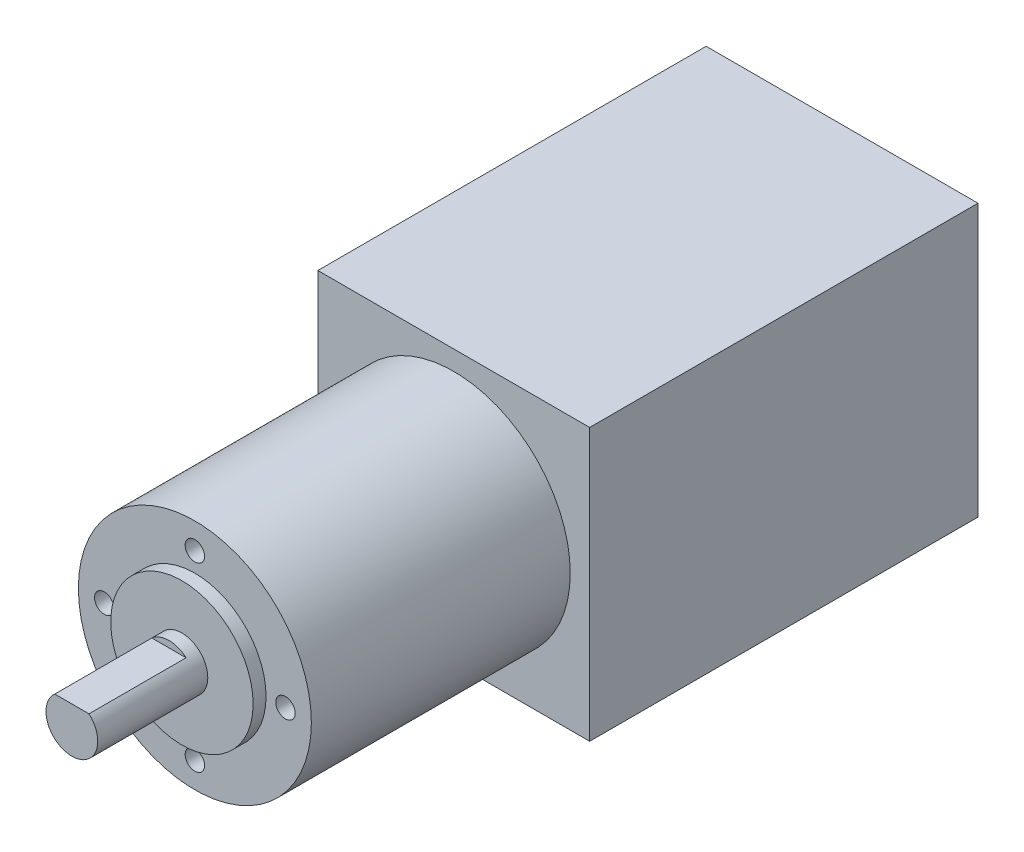
SolidWorks part; units mm, degrees
ref_plane "前视基准面" through (0, 0, 0) normal (0, 0, 1) x (1, 0, 0)
ref_plane "上视基准面" through (0, 0, 0) normal (0, 1, 0) x (1, 0, 0)
ref_plane "右视基准面" through (0, 0, 0) normal (1, 0, 0) x (0, 0, -1)
sketch "草图1" plane through (0, 0, 0) normal (0, 0, 1) x (1, 0, 0)
  line L1 (-21, 21) -> (21, 21)
  line L2 (-21, 21) -> (-21, -21)
  line L3 (-21, -21) -> (21, -21)
  line L4 (21, 21) -> (21, -21)
  line L5 (-21, 21) -> (21, -21) construction
  line L6 (-21, -21) -> (21, 21) construction
  point P0 (0, 0)
  dimension "D1" = 42
extrude "凸台-拉伸1" add sketch "草图1" along normal blind 60
sketch "草图2" plane through (0, 0, 60) normal (0, 0, 1) x (1, 0, 0)
  circle A0 centre (0, 0) radius 18
  dimension "D1" = 36
extrude "凸台-拉伸2" add sketch "草图2" along normal blind 40
sketch "草图3" plane through (0, 0, 100) normal (0, 0, 1) x (1, 0, 0)
  circle A0 centre (0, 0) radius 11
  dimension "D1" = 22
extrude "凸台-拉伸3" add sketch "草图3" along normal blind 2
sketch "草图4" plane through (0, 0, 102) normal (0, 0, 1) x (1, 0, 0)
  circle A0 centre (0, 0) radius 4
  dimension "D1" = 8
extrude "凸台-拉伸4" add sketch "草图4" along normal blind 17
sketch "草图5" plane through (0, 0, 100) normal (0, 0, 1) x (1, 0, 0)
  circle A5 centre (0, 0) radius 14 construction
  circle A6 centre (0, 14) radius 1.5
  circle A7 centre (14, 0) radius 1.5
  circle A8 centre (0, -14) radius 1.5
  circle A9 centre (-14, 0) radius 1.5
  dimension "D1" = 28
extrude "切除-拉伸1" cut sketch "草图5" against normal blind 4
sketch "草图6" plane through (0, 0, 119) normal (0, 0, 1) x (1, 0, 0)
  line L0 (0, 4) -> (0, 3) construction
  line L1 (2.6458, 3) -> (-2.6458, 3)
  circle A0 centre (0, 0) radius 4 construction
  arc A1 (-2.6458, 3) -> (2.6458, 3) centre (0, 0) cw
extrude "切除-拉伸2" cut sketch "草图6" against normal blind 15
